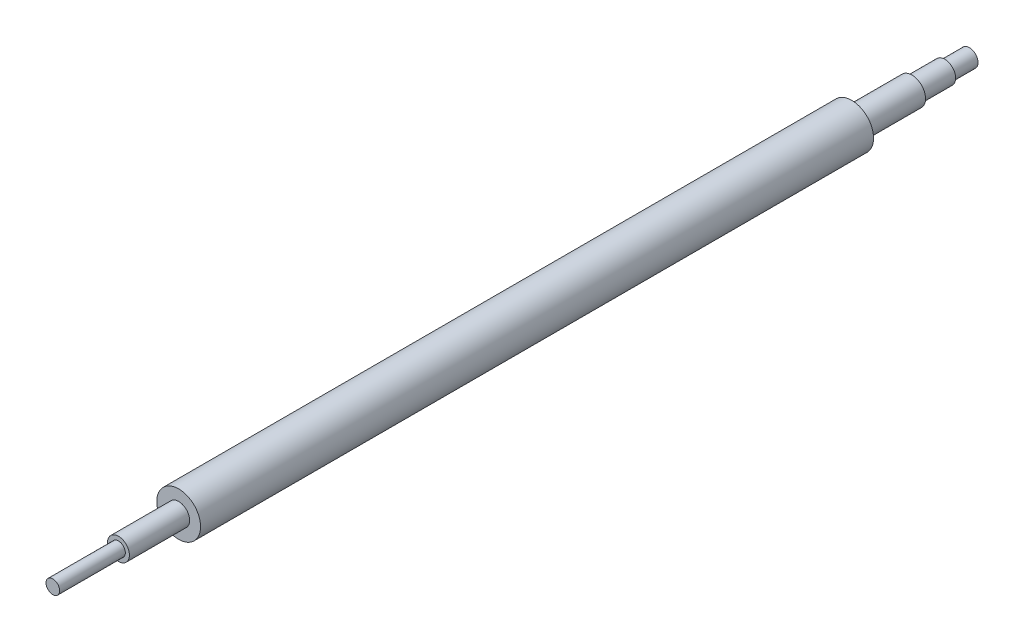
SolidWorks part; units mm, degrees
ref_plane "前视基准面" through (0, 0, 0) normal (0, 0, 1) x (1, 0, 0)
ref_plane "上视基准面" through (0, 0, 0) normal (0, 1, 0) x (1, 0, 0)
ref_plane "右视基准面" through (0, 0, 0) normal (1, 0, 0) x (0, 0, -1)
sketch "草图1" plane through (0, 0, 0) normal (0, 0, 1) x (1, 0, 0)
  circle A0 centre (0, 0) radius 8
  dimension "D1" = 16
extrude "凸台-拉伸1" add sketch "草图1" along normal blind 246
cosmetic thread "装饰螺纹线1" parameters "D1"=246, "D2"=15.999
sketch "草图2" plane through (0, 0, 246) normal (0, 0, 1) x (1, 0, 0)
  circle A0 centre (0, 0) radius 4
  dimension "D1" = 8
extrude "凸台-拉伸2" add sketch "草图2" along normal blind 22 separate body
sketch "草图4" plane through (0, 0, 0) normal (0, 0, -1) x (-1, 0, 0)
  circle A0 centre (0, 0) radius 5
  dimension "D1" = 10
extrude "凸台-拉伸3" add sketch "草图4" along normal blind 22 separate body
sketch "草图5" plane through (0, 0, 268) normal (0, 0, 1) x (1, 0, 0)
  circle A0 centre (0, 0) radius 2.5
  dimension "D1" = 5
extrude "凸台-拉伸4" add sketch "草图5" along normal blind 24
sketch "草图9" plane through (0, 0, -22) normal (0, 0, -1) x (-1, 0, 0)
  circle A0 centre (0, 0) radius 4
extrude "凸台-拉伸5" add sketch "草图9" along normal blind 12
sketch "草图10" plane through (0, 0, -34) normal (0, 0, -1) x (-1, 0, 0)
  circle A2 centre (0, 0) radius 3.175
extrude "凸台-拉伸6" add sketch "草图10" along normal blind 9
